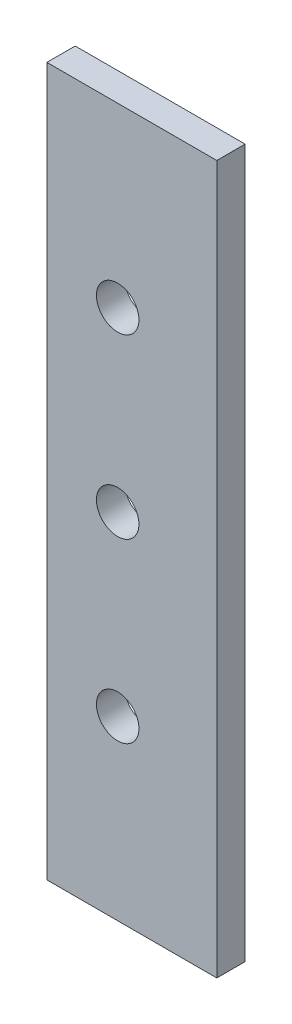
SolidWorks part; units mm, degrees
ref_plane "Front Plane" through (0, 0, 0) normal (0, 0, 1) x (1, 0, 0)
ref_plane "Top Plane" through (0, 0, 0) normal (0, 1, 0) x (1, 0, 0)
ref_plane "Right Plane" through (0, 0, 0) normal (1, 0, 0) x (0, 0, -1)
sketch "Sketch1" plane through (0, 0, 0) normal (0, 0, 1) x (1, 0, 0)
  line L0 (-18, 75) -> (18, -75) construction
  line L1 (-18, 75) -> (18, 75)
  line L2 (-18, 75) -> (-18, -75)
  line L3 (-18, -75) -> (18, -75)
  line L4 (18, 75) -> (18, -75)
  point P4 (0, 0)
  dimension "D1" = 36
  dimension "D2" = 150
extrude "Boss-Extrude1" add sketch "Sketch1" along normal blind 6
hole_wizard "M8 Clearance Hole1" positions "Sketch2" profile "Sketch3" hole size "M8" standard "ANSI Metric" end condition through all
sketch "Sketch2" plane through (0, 0, 6) normal (0, 0, 1) x (1, 0, 0)
  line L3 (-3, 0) -> (-3, 37.5) construction
  line L4 (-3, 37.5) -> (-3, 75) construction
  line L6 (-3, 0) -> (-3, -37.5) construction
  line L7 (-3, -37.5) -> (-3, -75) construction
  point P0 (-3, 37.5)
  point P2 (-3, 0)
  point P17 (-3, -37.5)
  point P28 (0, 0)
  dimension "D1" = 15
sketch "Sketch3" plane through (-3, 37.5, 6) normal (1, 0, 0) x (0, -1, 0)
  line L0 (0, 0) -> (0, 6)
  line L1 (0, 6) -> (4.5, 6)
  line L2 (4.5, 6) -> (4.5, 0)
  line L5 (4.5, 0) -> (0, 0)
  line L11 (0, -6.35) -> (0, 107.95) construction
  dimension "Thru Hole Dia." = 9
  dimension "Thru Hole Depth" = 6
